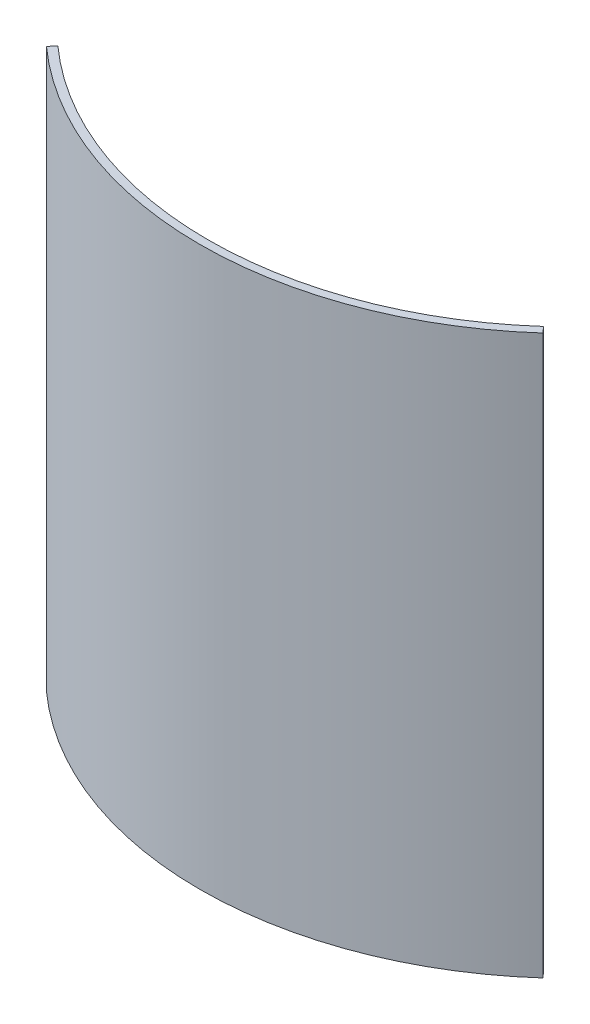
SolidWorks part; units mm, degrees
ref_plane "Front Plane" through (0, 0, 0) normal (0, 0, 1) x (1, 0, 0)
ref_plane "Top Plane" through (0, 0, 0) normal (0, 1, 0) x (1, 0, 0)
ref_plane "Right Plane" through (0, 0, 0) normal (1, 0, 0) x (0, 0, -1)
sketch "Sketch1" plane through (0, -1400, 0) normal (0, -1, 0) x (1, 0, 0)
  line L0 (-306.6667, 342.8638) -> (-300, 335.4102)
  line L1 (306.6667, 342.8638) -> (300, 335.4102)
  arc A0 (-306.6667, 342.8638) -> (306.6667, 342.8638) centre (0, 0) cw
  arc A1 (-300, 335.4102) -> (300, 335.4102) centre (0, 0) cw
  point P6 (0, 0)
  point P10 (0, 0)
  dimension "D1" = 10
extrude "Boss-Extrude1" add sketch "Sketch1" against normal offset from surface (690 mm away) 100 from surface at -100
